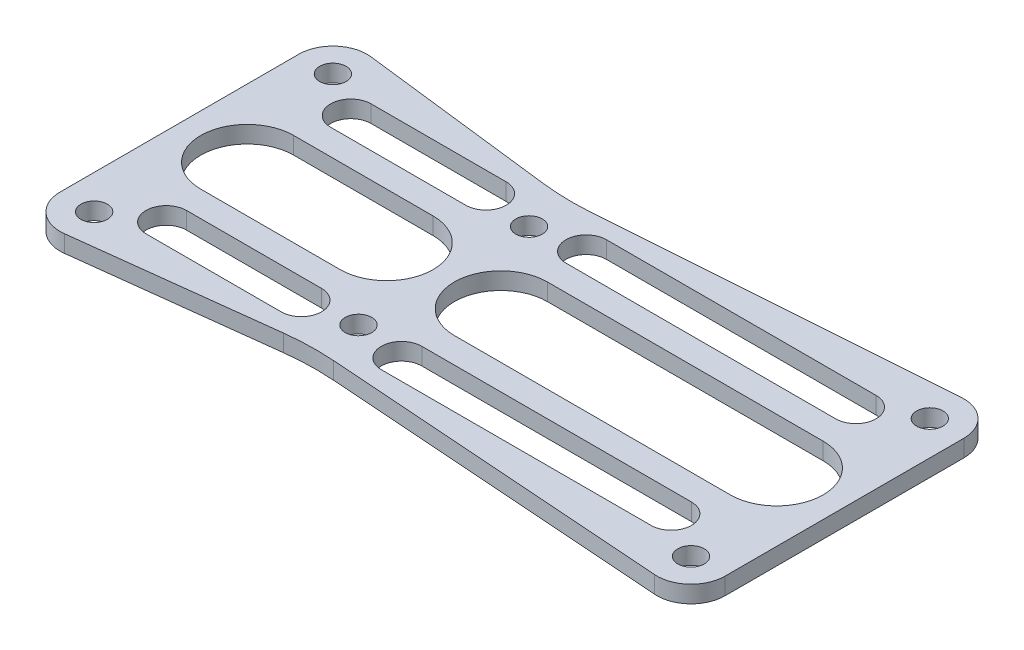
SolidWorks part; units mm, degrees
material "Thornel Mat VMA"
ref_plane "前视基准面" through (0, 0, 0) normal (0, 0, 1) x (1, 0, 0)
ref_plane "上视基准面" through (0, 0, 0) normal (0, 1, 0) x (1, 0, 0)
ref_plane "右视基准面" through (0, 0, 0) normal (1, 0, 0) x (0, 0, -1)
sketch "草图1" plane through (0, 0, 0) normal (0, 1, 0) x (1, 0, 0)
  line L1 (35, 18) -> (-35, 18)
  line L2 (39, 14) -> (39, -14)
  line L3 (35, -18) -> (-35, -18)
  line L4 (-39, 14) -> (-39, -14)
  line L5 (39, 18) -> (-39, -18) construction
  line L6 (39, -18) -> (-39, 18) construction
  arc A0 (39, 14) -> (35, 18) centre (35, 14) ccw
  arc A1 (39, -14) -> (35, -18) centre (35, -14) cw
  arc A2 (-35, -18) -> (-39, -14) centre (-35, -14) cw
  arc A3 (-35, 18) -> (-39, 14) centre (-35, 14) ccw
  point P0 (0, 0)
  dimension "D3" = 4
  dimension "D1" = 36
  dimension "D2" = 78
extrude "凸台-拉伸1" add sketch "草图1" along normal blind 2
sketch "草图2" plane through (0, 2, 0) normal (0, 1, 0) x (1, 0, 0)
  line L0 (-39, 0) -> (39, 0) construction
  line L1 (-39, 14) -> (-39, -14) construction
  line L2 (39, -14) -> (39, 14) construction
  line L3 (-8, 10) -> (-8, -10) construction
  point P8 (-8, 0)
  point P9 (-8.9095, 0)
  point P12 (-8, 10)
  point P13 (-8, -10)
  dimension "D1" = 20
  dimension "D2" = 43
hole_wizard "孔1" positions "草图3" profile "草图4" legacy end condition through all
sketch "草图3" plane through (0, 2, 0) normal (0, 1, 0) x (1, 0, 0)
  point P0 (-8, 10)
  point P3 (-8, -10)
  point P6 (-35, -14)
  point P9 (-35, 14)
  point P12 (35, 14)
  point P15 (35, -14)
sketch "草图4" plane through (-8, 2, -10) normal (1, 0, 0) x (0, 0, 1)
  line L0 (0, 0) -> (0, 2)
  line L1 (0, 2) -> (1.55, 2)
  line L2 (1.55, 2) -> (1.55, 0)
  line L3 (1.55, 0) -> (0, 0)
  line L4 (0, 110) -> (0, -10) construction
  dimension "直径" = 3.1
  dimension "深度" = 2
sketch "草图5" plane through (0, 2, 0) normal (0, 1, 0) x (1, 0, 0)
  line L0 (-8, 44.8501) -> (-8, 10) construction
  line L1 (-11.5601, 15.2131) -> (-34.5229, 17.9714)
  line L2 (-5.8625, 15.0766) -> (34.7136, 17.9897)
  line L3 (-39, 14) -> (-39, -14)
  line L4 (-39, 14) -> (-39, -14) construction
  line L5 (-39, 0) -> (39, 0) construction
  line L6 (39, -14) -> (39, 14) construction
  line L7 (39, 14) -> (39, -14)
  line L8 (-5.8625, -15.0766) -> (34.7136, -17.9897)
  line L9 (-11.5601, -15.2131) -> (-34.5229, -17.9714)
  line L11 (51.0278, -27.606) -> (-51.0278, -27.606)
  line L12 (51.0278, -27.606) -> (51.0278, 27.606)
  line L13 (51.0278, 27.606) -> (-51.0278, 27.606)
  line L14 (-51.0278, -27.606) -> (-51.0278, 27.606)
  line L15 (51.0278, -27.606) -> (-51.0278, 27.606) construction
  line L16 (51.0278, 27.606) -> (-51.0278, -27.606) construction
  arc A0 (-11.5601, 15.2131) -> (-5.8625, 15.0766) centre (-8, 44.8501) ccw
  arc A1 (-34.5229, 17.9714) -> (-39, 14) centre (-35, 14) ccw
  arc A2 (39, 14) -> (34.7136, 17.9897) centre (35, 14) ccw
  arc A3 (39, 14) -> (35, 18) centre (35, 14) ccw construction
  arc A4 (39, -14) -> (34.7136, -17.9897) centre (35, -14) cw
  arc A5 (-34.5229, -17.9714) -> (-39, -14) centre (-35, -14) cw
  arc A6 (-11.5601, -15.2131) -> (-5.8625, -15.0766) centre (-8, -44.8501) cw
  point P11 (-8, 15)
  point P35 (-8, -15)
  point P36 (0, 0)
  dimension "D1" = 5
extrude "切除-拉伸1" cut sketch "草图5" against normal through all both and the other way through all
sketch "草图6" plane through (0, 2, 0) normal (0, 1, 0) x (1, 0, 0)
  line L0 (-11.5, 10.825) -> (-11.5, -10.825) construction
  line L1 (-4.5, 10.825) -> (-4.5, -10.825) construction
  line L2 (-31.05, 0) -> (-14.7, 0) construction
  line L4 (-2.125, 10.825) -> (29.5059, 10.825) construction
  line L5 (-2.125, 13.2) -> (29.5059, 13.2)
  line L6 (-2.125, 8.45) -> (29.5059, 8.45)
  line L7 (-13.875, 10.825) -> (-29.7196, 10.825) construction
  line L8 (-13.875, 8.45) -> (-29.7196, 8.45)
  line L9 (-13.875, 13.2) -> (-29.7196, 13.2)
  line L10 (-39, 0) -> (39, 0) construction
  line L11 (-39, 14) -> (-39, -14) construction
  line L12 (-2.125, -10.825) -> (29.5059, -10.825) construction
  line L13 (-2.125, -13.2) -> (29.5059, -13.2)
  line L14 (-2.125, -8.45) -> (29.5059, -8.45)
  line L15 (-13.875, -10.825) -> (-29.7196, -10.825) construction
  line L16 (-13.875, -8.45) -> (-29.7196, -8.45)
  line L17 (-13.875, -13.2) -> (-29.7196, -13.2)
  line L18 (-31.05, 5.45) -> (-14.7, 5.45)
  line L19 (-31.05, -5.45) -> (-14.7, -5.45)
  line L20 (-8, 10) -> (-8, -10) construction
  line L21 (-1.3, 0) -> (31.05, 0) construction
  line L22 (-1.3, 5.45) -> (31.05, 5.45)
  line L23 (-1.3, -5.45) -> (31.05, -5.45)
  line L24 (39, -14) -> (39, 14) construction
  arc A0 (-31.05, 5.45) -> (-31.05, -5.45) centre (-31.05, 0) ccw
  arc A1 (-14.7, -5.45) -> (-14.7, 5.45) centre (-14.7, 0) ccw
  arc A2 (-2.125, 13.2) -> (-2.125, 8.45) centre (-2.125, 10.825) ccw
  arc A3 (29.5059, 8.45) -> (29.5059, 13.2) centre (29.5059, 10.825) ccw
  circle A4 centre (-8, 10) radius 1.55 construction
  arc A5 (-13.875, 8.45) -> (-13.875, 13.2) centre (-13.875, 10.825) ccw
  arc A6 (-29.7196, 13.2) -> (-29.7196, 8.45) centre (-29.7196, 10.825) ccw
  arc A7 (-2.125, -13.2) -> (-2.125, -8.45) centre (-2.125, -10.825) cw
  arc A8 (29.5059, -8.45) -> (29.5059, -13.2) centre (29.5059, -10.825) cw
  arc A9 (-13.875, -8.45) -> (-13.875, -13.2) centre (-13.875, -10.825) cw
  arc A10 (-29.7196, -13.2) -> (-29.7196, -8.45) centre (-29.7196, -10.825) cw
  arc A11 (-1.3, 5.45) -> (-1.3, -5.45) centre (-1.3, 0) ccw
  arc A12 (31.05, -5.45) -> (31.05, 5.45) centre (31.05, 0) ccw
  point P5 (-8, 10)
  point P8 (-22.875, 0)
  point P13 (13.6904, 10.825)
  point P20 (-21.7973, 10.825)
  point P33 (13.6904, -10.825)
  point P40 (-21.7973, -10.825)
  point P48 (-9.25, 0)
  point P54 (14.875, 0)
  point P59 (-36.5, 0)
  point P60 (-6.75, 0)
  point P65 (36.5, 0)
  dimension "D5" = 2.5
  dimension "D1" = 3.5
  dimension "D2" = 4.75
  dimension "D3" = 3.5
  dimension "D4" = 3
  dimension "D6" = 2.5
  dimension "D7" = 2.5
  dimension "D8" = 2.5
extrude "切除-拉伸2" cut sketch "草图6" against normal through all both and the other way through all
